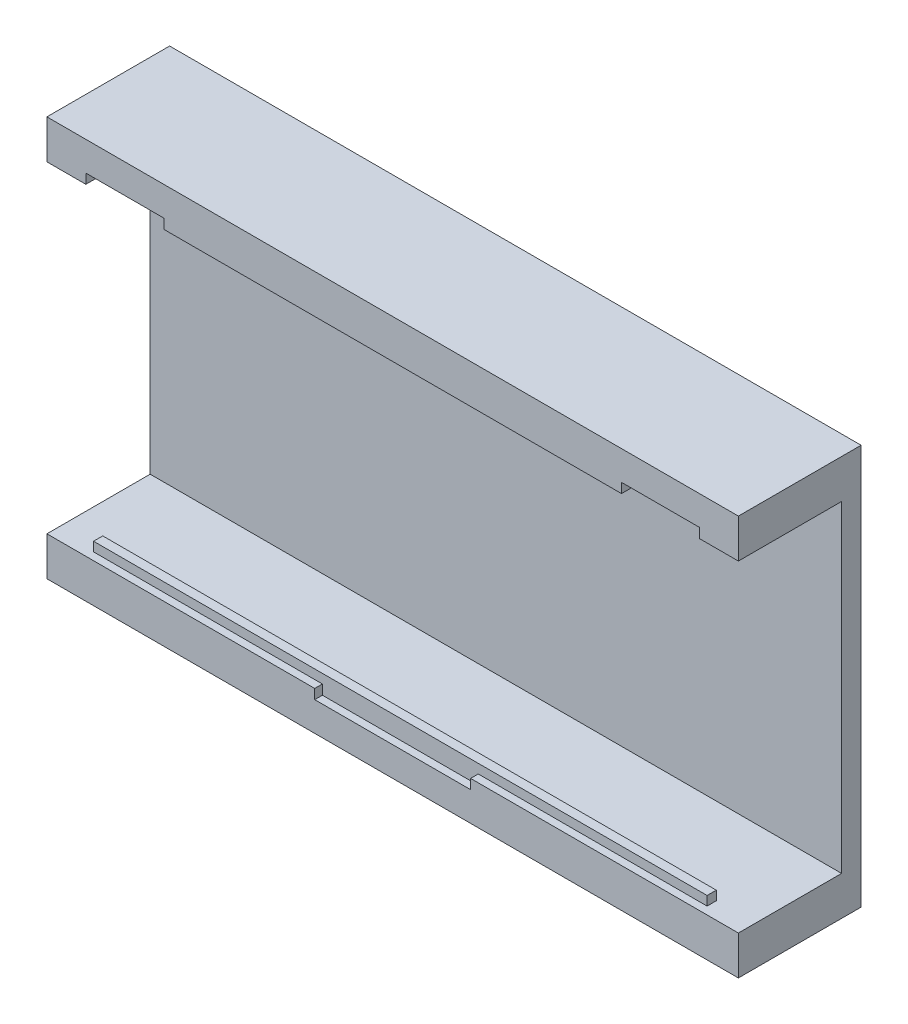
SolidWorks part; units mm, degrees
ref_plane "Front Plane" through (0, 0, 0) normal (0, 0, 1) x (1, 0, 0)
ref_plane "Top Plane" through (0, 0, 0) normal (0, 1, 0) x (1, 0, 0)
ref_plane "Right Plane" through (0, 0, 0) normal (1, 0, 0) x (0, 0, -1)
ref_plane "Plane1"
sketch "Sketch1" plane through (0, 0, 0) normal (0, 0, 1) x (1, 0, 0)
  line L0 (-112.7, 65.2) -> (112.7, 65.2)
  line L1 (112.7, 65.2) -> (112.7, -65.2)
  line L2 (112.7, -65.2) -> (-112.7, -65.2)
  line L3 (-112.7, -65.2) -> (-112.7, 65.2)
  line L4 (-100, -52.5) -> (100, -52.5)
  line L5 (100, -52.5) -> (100, 52.5)
  line L6 (100, 52.5) -> (-100, 52.5)
  line L7 (-100, 52.5) -> (-100, -52.5)
  dimension "D1" = 200
  dimension "D2" = 105
  dimension "D3" = 12.7
extrude "Extrusion1" add sketch "Sketch1" against normal blind 40 contours L3 L2 L1 L0 L7 L6 L5 L4
sketch "Sketch2" plane through (0, 52.5, 0) normal (0, -1, 0) x (1, 0, 0)
  line L0 (100, -40) -> (100, -33.65)
  line L1 (100, -33.65) -> (-100, -33.65)
  line L2 (-100, -33.65) -> (-100, -40)
  line L3 (-100, -40) -> (100, -40)
  dimension "D1" = 90
extrude "Extrusion2" add sketch "Sketch2" along normal up to next
sketch "Sketch3" plane through (0, 0, -40) normal (0, 0, -1) x (-1, 0, 0)
  line L0 (2.5, 43.2) -> (2.5, 39.5301)
  line L1 (-2.5, 39.5301) -> (-2.5, 43.2)
  arc A0 (-2.5, 39.5301) -> (2.5, 39.5301) centre (0, 35.2) ccw
  arc A1 (2.5, 43.2) -> (-2.5, 43.2) centre (0, 43.2) ccw
  dimension "D1" = 10
  dimension "D2" = 5
  dimension "D3" = 8
extrude "Extrusion4" cut sketch "Sketch3" against normal through all
sketch "Sketch4" plane through (100, 0, 0) normal (-1, 0, 0) x (0, 0, 1)
  line L0 (-33.65, -52.5) -> (-26.15, -52.5)
  line L1 (-26.15, -52.5) -> (-26.15, -47.5)
  line L2 (-26.15, -47.5) -> (-33.65, -47.5)
  line L3 (-33.65, -47.5) -> (-33.65, -52.5)
  dimension "D1" = 7.5
  dimension "D2" = 5
extrude "Extrusion5" cut sketch "Sketch4" against normal through all
sketch "Sketch5" plane through (-100, 0, 0) normal (1, 0, 0) x (0, 0, -1)
  line L0 (2.5, -52.5) -> (5.5, -52.5)
  line L1 (5.5, -52.5) -> (5.5, -49.5)
  line L2 (5.5, -49.5) -> (2.5, -49.5)
  line L3 (2.5, -49.5) -> (2.5, -52.5)
  line L4 (33.65, -52.5) -> (0, -52.5) construction
  dimension "D1" = 90
  dimension "D2" = 3
  dimension "D3" = 3
extrude "Extrusion6" add sketch "Sketch5" along normal up to next
ref_plane "Plane2" through (0, 0, 0) normal (0, 0, 1) x (1, 0, 0)
sketch "Sketch6" plane through (0, 0, 0) normal (0, 0, 1) x (1, 0, 0)
  line L0 (25.4, -52.5) -> (-25.4, -52.5)
  line L1 (-25.4, -52.5) -> (-25.4, -55.675)
  line L2 (-25.4, -55.675) -> (25.4, -55.675)
  line L3 (25.4, -55.675) -> (25.4, -52.5)
  dimension "D1" = 50.8
extrude "Extrusion7" cut sketch "Sketch6" against normal up to surface (2.5 mm away) up to face at (0, -51, -2.5)
ref_plane "Plane3" through (0, 0, 0) normal (0, 0, 1) x (1, 0, 0)
sketch "Sketch7" plane through (0, 0, 0) normal (0, 0, 1) x (1, 0, 0)
  line L0 (-100, 52.5) -> (-74.6, 52.5)
  line L1 (-74.6, 52.5) -> (-74.6, 55.675)
  line L2 (-74.6, 55.675) -> (-100, 55.675)
  line L3 (-100, 55.675) -> (-100, 52.5)
  dimension "D1" = 25.4
  dimension "D2" = 3.175
extrude "Extrusion8" cut sketch "Sketch7" against normal blind 22.86
ref_plane "Plane4" through (0, 0, 0) normal (1, 0, 0) x (0, 1, 0)
mirror "Mirror1" about plane through (0, 0, 0) normal (1, 0, 0) of "Extrusion8"
sketch "Sketch8" plane through (0, -52.5, 0) normal (0, 1, 0) x (-1, 0, 0)
  line L0 (0, -33.65) -> (3.7465, -33.65)
  line L1 (3.7465, -33.65) -> (3.7465, -28.6462)
  line L2 (3.7465, -28.6462) -> (-3.7465, -28.6462)
  line L3 (-3.7465, -28.6462) -> (-3.7465, -33.65)
  line L4 (-3.7465, -33.65) -> (0, -33.65)
  dimension "D1" = 7.493
  dimension "D2" = 5.0038
extrude "Extrusion9" cut sketch "Sketch8" against normal through all
sketch "Sketch10" plane through (-100, 0, 0) normal (1, 0, 0) x (0, 0, -1)
  line L1 (0, -65.2) -> (40, -65.2)
  line L2 (0, -65.2) -> (0, 52.5)
  line L3 (0, 52.5) -> (40, 52.5)
  line L4 (40, -65.2) -> (40, 52.5)
  line L8 (0, 65.2) -> (0, -65.2)
  line L9 (40, 65.2) -> (0, 65.2)
  line L10 (40, -65.2) -> (40, 65.2)
  line L11 (0, -65.2) -> (40, -65.2)
  line L12 (0, 52.5) -> (0, -65.2) construction
  line L17 (5.5, -52.5) -> (33.65, -52.5)
  line L18 (33.65, -52.5) -> (33.65, 52.5)
  line L19 (33.65, 52.5) -> (22.86, 52.5)
  line L20 (22.86, 52.5) -> (22.86, 55.675)
  line L21 (22.86, 55.675) -> (0, 55.675)
  line L22 (0, 55.675) -> (0, -52.5)
  line L27 (5.5, -52.5) -> (33.65, -52.5) construction
  line L28 (33.65, -52.5) -> (33.65, 52.5) construction
  line L29 (33.65, 52.5) -> (22.86, 52.5) construction
  line L30 (22.86, 52.5) -> (22.86, 55.675) construction
  line L31 (22.86, 55.675) -> (0, 55.675) construction
  line L32 (0, 55.675) -> (0, -52.5) construction
  line L34 (40, -65.2) -> (40, 68.5658) construction
  line L35 (0, -65.2) -> (40, -65.2) construction
  line L38 (2.5, -52.5) -> (2.5, -49.5)
  line L39 (2.5, -52.5) -> (2.5, -49.5)
  line L40 (2.5, -49.5) -> (5.5, -49.5)
  line L41 (2.5, -49.5) -> (5.5, -49.5)
  line L42 (5.5, -49.5) -> (5.5, -52.5)
  line L43 (5.5, -49.5) -> (5.5, -52.5)
  line L44 (0, -52.5) -> (2.5, -52.5)
  line L45 (0, -52.5) -> (2.5, -52.5)
  dimension "D1" = 0
  dimension "D2" = 0
sketch "Sketch14" plane through (-100, 0, 0) normal (1, 0, 0) x (0, 0, -1)
  line L1 (0, 52.5) -> (40, 52.5)
  line L2 (0, 52.5) -> (0, 65.2)
  line L3 (0, 65.2) -> (40, 65.2)
  line L4 (40, 52.5) -> (40, 65.2)
  line L7 (33.65, 52.5) -> (22.86, 52.5)
  line L8 (22.86, 52.5) -> (22.86, 55.675)
  line L9 (22.86, 55.675) -> (0, 55.675)
  line L10 (0, 55.675) -> (0, -52.5)
  line L13 (33.65, 52.5) -> (22.86, 52.5) construction
  line L14 (22.86, 52.5) -> (22.86, 55.675) construction
  line L15 (22.86, 55.675) -> (0, 55.675) construction
  line L16 (0, 55.675) -> (0, -52.5) construction
  line L18 (0, -65.2) -> (40, -65.2)
  line L19 (0, -65.2) -> (40, -65.2)
  line L20 (0, 65.2) -> (0, -65.2)
  line L21 (40, 65.2) -> (0, 65.2)
  line L22 (40, -65.2) -> (40, 65.2)
  line L24 (0, 65.2) -> (0, -65.2) construction
  line L25 (40, 65.2) -> (0, 65.2) construction
  line L26 (40, -65.2) -> (40, 65.2) construction
  line L33 (33.65, -52.5) -> (33.65, 52.5)
  line L34 (33.65, -52.5) -> (33.65, 52.5)
  line L35 (0, -52.5) -> (2.5, -52.5)
  line L36 (0, -52.5) -> (2.5, -52.5)
  line L37 (2.5, -52.5) -> (2.5, -49.5)
  line L38 (2.5, -52.5) -> (2.5, -49.5)
  line L39 (2.5, -49.5) -> (5.5, -49.5)
  line L40 (2.5, -49.5) -> (5.5, -49.5)
  line L41 (5.5, -49.5) -> (5.5, -52.5)
  line L42 (5.5, -49.5) -> (5.5, -52.5)
  line L43 (5.5, -52.5) -> (33.65, -52.5)
  line L44 (5.5, -52.5) -> (33.65, -52.5)
  point P11 (39.8044, 64.979)
  dimension "D1" = 0
  dimension "D2" = 0
sketch "Sketch17" plane through (-100, 0, 0) normal (1, 0, 0) x (0, 0, -1)
  line L1 (40, 65.2) -> (0, 65.2)
  line L2 (40, 65.2) -> (40, -52.5)
  line L3 (40, -52.5) -> (0, -52.5)
  line L4 (0, 65.2) -> (0, -65.2)
  line L5 (40, 65.2) -> (0, 65.2)
  line L6 (40, -65.2) -> (40, 65.2)
  line L7 (0, -65.2) -> (40, -65.2)
  line L8 (0, 65.2) -> (0, -65.2) construction
  line L9 (40, 65.2) -> (0, 65.2) construction
  line L10 (2.5, -52.5) -> (2.5, -49.5)
  line L11 (2.5, -49.5) -> (5.5, -49.5)
  line L12 (5.5, -49.5) -> (5.5, -52.5)
  line L13 (5.5, -52.5) -> (33.65, -52.5)
  line L14 (33.65, -52.5) -> (33.65, 52.5)
  line L15 (33.65, 52.5) -> (22.86, 52.5)
  line L16 (22.86, 52.5) -> (22.86, 55.675)
  line L17 (22.86, 55.675) -> (0, 55.675)
  line L18 (0, 55.675) -> (0, -52.5)
  line L19 (0, -52.5) -> (2.5, -52.5)
  line L20 (2.5, -52.5) -> (2.5, -49.5) construction
  line L21 (2.5, -49.5) -> (5.5, -49.5) construction
  line L22 (5.5, -49.5) -> (5.5, -52.5) construction
  line L23 (5.5, -52.5) -> (33.65, -52.5) construction
  line L24 (33.65, -52.5) -> (33.65, 52.5) construction
  line L25 (33.65, 52.5) -> (22.86, 52.5) construction
  line L26 (22.86, 52.5) -> (22.86, 55.675) construction
  line L27 (22.86, 55.675) -> (0, 55.675) construction
  line L28 (0, 55.675) -> (0, -52.5) construction
  line L29 (0, -52.5) -> (2.5, -52.5) construction
  line L30 (40, -65.2) -> (40, 65.2) construction
  line L31 (0, -65.2) -> (40, -65.2) construction
  line L32 (0, 65.2) -> (0, -52.5)
  dimension "D1" = 0
  dimension "D2" = 0
sketch "Sketch20" plane through (0, 0, 0) normal (0, 0, 1) x (1, 0, 0)
  line L1 (-100, 52.5) -> (-112.7, 52.5)
  line L2 (-100, 52.5) -> (-100, -52.5)
  line L3 (-100, -52.5) -> (-112.7, -52.5)
  line L4 (-112.7, 65.2) -> (-112.7, -65.2)
  line L5 (-112.7, -65.2) -> (112.7, -65.2)
  line L6 (112.7, -65.2) -> (112.7, 65.2)
  line L7 (112.7, 65.2) -> (-112.7, 65.2)
  line L8 (-112.7, 65.2) -> (-112.7, -65.2) construction
  line L9 (-112.7, -65.2) -> (112.7, -65.2) construction
  line L10 (112.7, -65.2) -> (112.7, 65.2) construction
  line L11 (112.7, 65.2) -> (-112.7, 65.2) construction
  line L12 (-112.7, 52.5) -> (-112.7, -52.5)
  line L13 (100, 52.5) -> (112.7, 52.5)
  line L14 (100, 52.5) -> (100, -52.5)
  line L15 (100, -52.5) -> (112.7, -52.5)
  line L16 (112.7, 52.5) -> (112.7, -52.5)
  line L18 (3.7465, -52.5) -> (112.7, -52.5)
  line L19 (112.7, -52.5) -> (112.7, -47.5)
  line L20 (112.7, -47.5) -> (100, -47.5)
  line L21 (100, -47.5) -> (100, 52.5)
  line L22 (100, 52.5) -> (-100, 52.5)
  line L23 (-100, 52.5) -> (-100, -52.5)
  line L24 (-100, -52.5) -> (-3.7465, -52.5)
  line L25 (-3.7465, -52.5) -> (-3.7465, -65.2)
  line L26 (-3.7465, -65.2) -> (3.7465, -65.2)
  line L27 (3.7465, -65.2) -> (3.7465, -52.5)
  line L28 (3.7465, -52.5) -> (112.7, -52.5) construction
  line L29 (112.7, -52.5) -> (112.7, -47.5) construction
  line L30 (112.7, -47.5) -> (100, -47.5) construction
  line L31 (100, -47.5) -> (100, 52.5) construction
  line L32 (100, 52.5) -> (-100, 52.5) construction
  line L33 (-100, 52.5) -> (-100, -52.5) construction
  line L34 (-100, -52.5) -> (-3.7465, -52.5) construction
  line L35 (-3.7465, -52.5) -> (-3.7465, -65.2) construction
  line L36 (-3.7465, -65.2) -> (3.7465, -65.2) construction
  line L37 (3.7465, -65.2) -> (3.7465, -52.5) construction
  dimension "D1" = 0
  dimension "D2" = 0
extrude "Cut-Extrude425" cut sketch "Sketch20" against normal up to surface (33.65 mm away) up to face at (0, 39.6575, -33.65)
sketch "Sketch21" plane through (-3.7465, 0, 0) normal (1, 0, 0) x (0, 0, -1)
  line L4 (33.65, -52.5) -> (28.6462, -52.5)
  line L5 (28.6462, -52.5) -> (28.6462, -65.2)
  line L6 (28.6462, -65.2) -> (33.65, -65.2)
  line L7 (33.65, -65.2) -> (33.65, -52.5)
  line L8 (33.65, -52.5) -> (28.6462, -52.5)
  line L9 (28.6462, -52.5) -> (28.6462, -65.2)
  line L10 (28.6462, -65.2) -> (33.65, -65.2)
  line L11 (33.65, -65.2) -> (33.65, -52.5)
  dimension "D1" = 0
extrude "Boss-Extrude4" add sketch "Sketch21" along normal up to next
